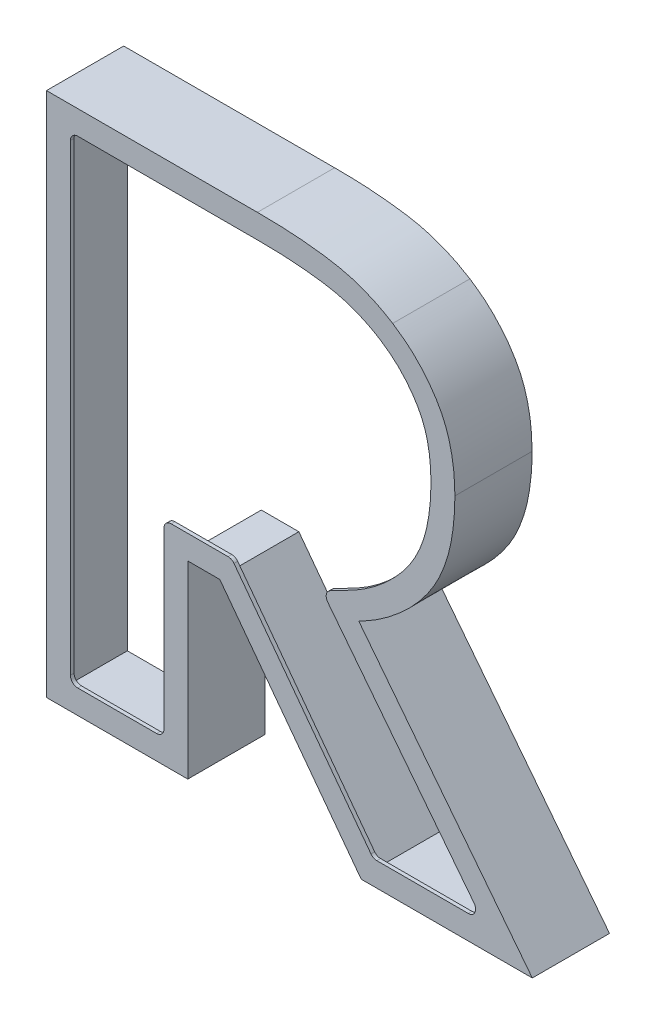
SolidWorks part; units mm, degrees
ref_plane "Front Plane" through (0, 0, 0) normal (0, 0, 1) x (1, 0, 0)
ref_plane "Top Plane" through (0, 0, 0) normal (0, 1, 0) x (1, 0, 0)
ref_plane "Right Plane" through (0, 0, 0) normal (1, 0, 0) x (0, 0, -1)
sketch "Sketch1" plane through (0, 0, 0) normal (0, 0, 1) x (1, 0, 0)
  line L65 (2984.2848, -1502.5826) -> (2926.9066, -1502.5826)
  line L66 (3059.0757, -1645.5826) -> (3011.8589, -1585.1045)
  line L67 (3012.5251, -1645.5826) -> (3059.0757, -1645.5826)
  line L68 (2974.0639, -1594.1902) -> (3012.5251, -1645.5826)
  line L69 (2965.3497, -1594.1902) -> (2974.0639, -1594.1902)
  line L70 (2965.3497, -1645.5826) -> (2965.3497, -1594.1902)
  line L71 (2926.9066, -1502.5826) -> (2926.9066, -1645.5826)
  line L72 (2926.9066, -1645.5826) -> (2965.3497, -1645.5826)
  line L73 (2984.2848, -1502.5826) -> (2926.9066, -1502.5826)
  line L74 (3059.0757, -1645.5826) -> (3011.8589, -1585.1045)
  line L75 (3012.5251, -1645.5826) -> (3059.0757, -1645.5826)
  line L76 (2974.0639, -1594.1902) -> (3012.5251, -1645.5826)
  line L77 (2965.3497, -1594.1902) -> (2974.0639, -1594.1902)
  line L78 (2965.3497, -1645.5826) -> (2965.3497, -1594.1902)
  line L79 (2926.9066, -1502.5826) -> (2926.9066, -1645.5826)
  line L80 (2926.9066, -1645.5826) -> (2965.3497, -1645.5826)
  spline S12 degree 3 poles (4010.2252, 226.3822) (3055.0458, -1622.3728) (3054.8193, -1526.8514) (3015.5085, -1507.3041) (3014.0398, -1506.6932) (3011.791, -1505.8699) (3011.0366, -1505.6141) (3009.5173, -1505.1475) (3008.752, -1504.9375) (3006.4396, -1504.3769) (3004.8773, -1504.0899) (3001.7298, -1503.6105) (3000.1482, -1503.4184) (2996.9859, -1503.0865) (2995.4028, -1502.9517) (2992.2324, -1502.7488) (2990.6451, -1502.6808) (2920.7722, -1501.0072) (2849.3372, -1549.2207) (2910.0267, 492.5285) knots -3.206592 -3.206592 -3.206592 -3.206592 0.125 0.125 0.25 0.25 0.3125 0.3125 0.375 0.375 0.5 0.5 0.625 0.625 0.75 0.75 0.875 0.875 6.24585 6.24585 6.24585 6.24585 only from (3021.0882, -1510.3488) to (2984.2848, -1502.5826)
  spline S13 degree 3 poles (5028.8784, -1369.879) (2970.5907, -1642.9502) (3041.5752, -1584.5412) (3037.6687, -1536.1925) (3037.4469, -1534.6286) (3036.9787, -1532.3038) (3036.8014, -1531.5321) (3036.3993, -1529.9963) (3036.1734, -1529.2322) (3035.7857, -1528.0937) (3035.648, -1527.7149) (3035.3574, -1526.9685) (3035.2042, -1526.6001) (3034.7222, -1525.5079) (3034.3715, -1524.7971) (3033.2459, -1522.7083) (3032.402, -1521.371) (3031.0037, -1519.4436) (3030.5147, -1518.8147) (3029.4925, -1517.583) (3028.9623, -1516.984) (3027.3291, -1515.2424) (3026.1832, -1514.1467) (2993.5272, -1487.5279) (2903.1028, -1529.3957) (4246.4092, 68.7534) knots -3.578397 -3.578397 -3.578397 -3.578397 0.125 0.125 0.25 0.25 0.3125 0.3125 0.375 0.375 0.40625 0.40625 0.4375 0.4375 0.5 0.5 0.625 0.625 0.6875 0.6875 0.75 0.75 0.875 0.875 4.072965 4.072965 4.072965 4.072965 only from (3038.0082, -1542.5336) to (3021.0882, -1510.3488)
  spline S14 degree 3 poles (4034.7201, -3301.2243) (2880.5558, -1576.6127) (2968.7745, -1609.9372) (3015.7268, -1582.9688) (3016.663, -1582.3914) (3018.488, -1581.1693) (3019.3784, -1580.5271) (3021.1207, -1579.1881) (3021.9731, -1578.492) (3023.2238, -1577.4084) (3023.6359, -1577.0404) (3024.4498, -1576.2899) (3024.8522, -1575.9067) (3026.0366, -1574.7407) (3026.7961, -1573.9403) (3028.2531, -1572.292) (3028.9507, -1571.4442) (3030.2824, -1569.7001) (3030.9178, -1568.8046) (3032.1132, -1566.9561) (3032.671, -1566.0013) (3033.6978, -1564.0237) (3034.1575, -1563.0166) (3034.9889, -1560.9765) (3035.3648, -1559.9441) (3036.0401, -1557.8555) (3036.3372, -1556.7985) (3036.8466, -1554.6582) (3037.0571, -1553.5743) (3037.3186, -1551.9316) (3037.3974, -1551.381) (3037.5426, -1550.28) (3037.6098, -1549.7291) (3037.7908, -1548.075) (3037.8815, -1546.9701) (3039.8713, -1502.1646) (2987.2068, -1454.5687) (5036.4914, -1557.0312) knots -2.944012 -2.944012 -2.944012 -2.944012 0.0625 0.0625 0.125 0.125 0.1875 0.1875 0.25 0.25 0.28125 0.28125 0.3125 0.3125 0.375 0.375 0.4375 0.4375 0.5 0.5 0.5625 0.5625 0.625 0.625 0.6875 0.6875 0.75 0.75 0.8125 0.8125 0.84375 0.84375 0.875 0.875 0.9375 0.9375 3.402691 3.402691 3.402691 3.402691 only from (3011.8589, -1585.1045) to (3038.0082, -1542.5336)
  spline S15 degree 3 poles (3021.0882, -1510.3488) (3019.7203, -1509.5327) (3018.3517, -1508.7179) (3015.5085, -1507.3041) (3014.0398, -1506.6932) (3011.791, -1505.8699) (3011.0366, -1505.6141) (3009.5173, -1505.1475) (3008.752, -1504.9375) (3006.4396, -1504.3769) (3004.8773, -1504.0899) (3001.7298, -1503.6105) (3000.1482, -1503.4184) (2996.9859, -1503.0865) (2995.4028, -1502.9517) (2992.2324, -1502.7488) (2990.6451, -1502.6808) (2987.4667, -1502.6047) (2985.8757, -1502.5936) (2984.2848, -1502.5826) knots 0 0 0 0 0.125 0.125 0.25 0.25 0.3125 0.3125 0.375 0.375 0.5 0.5 0.625 0.625 0.75 0.75 0.875 0.875 1 1 1 1
  spline S16 degree 3 poles (3038.0082, -1542.5336) (3037.9662, -1540.9417) (3037.9238, -1539.3498) (3037.6687, -1536.1925) (3037.4469, -1534.6286) (3036.9787, -1532.3038) (3036.8014, -1531.5321) (3036.3993, -1529.9963) (3036.1734, -1529.2322) (3035.7857, -1528.0937) (3035.648, -1527.7149) (3035.3574, -1526.9685) (3035.2042, -1526.6001) (3034.7222, -1525.5079) (3034.3715, -1524.7971) (3033.2459, -1522.7083) (3032.402, -1521.371) (3031.0037, -1519.4436) (3030.5147, -1518.8147) (3029.4925, -1517.583) (3028.9623, -1516.984) (3027.3291, -1515.2424) (3026.1832, -1514.1467) (3023.7263, -1512.1441) (3022.4078, -1511.2458) (3021.0882, -1510.3488) knots 0 0 0 0 0.125 0.125 0.25 0.25 0.3125 0.3125 0.375 0.375 0.40625 0.40625 0.4375 0.4375 0.5 0.5 0.625 0.625 0.6875 0.6875 0.75 0.75 0.875 0.875 1 1 1 1
  spline S17 degree 3 poles (3011.8589, -1585.1045) (3012.84, -1584.5906) (3013.8144, -1584.0672) (3015.7268, -1582.9688) (3016.663, -1582.3914) (3018.488, -1581.1693) (3019.3784, -1580.5271) (3021.1207, -1579.1881) (3021.9731, -1578.492) (3023.2238, -1577.4084) (3023.6359, -1577.0404) (3024.4498, -1576.2899) (3024.8522, -1575.9067) (3026.0366, -1574.7407) (3026.7961, -1573.9403) (3028.2531, -1572.292) (3028.9507, -1571.4442) (3030.2824, -1569.7001) (3030.9178, -1568.8046) (3032.1132, -1566.9561) (3032.671, -1566.0013) (3033.6978, -1564.0237) (3034.1575, -1563.0166) (3034.9889, -1560.9765) (3035.3648, -1559.9441) (3036.0401, -1557.8555) (3036.3372, -1556.7985) (3036.8466, -1554.6582) (3037.0571, -1553.5743) (3037.3186, -1551.9316) (3037.3974, -1551.381) (3037.5426, -1550.28) (3037.6098, -1549.7291) (3037.7908, -1548.075) (3037.8815, -1546.9701) (3037.9799, -1544.7543) (3037.994, -1543.644) (3038.0082, -1542.5336) knots 0 0 0 0 0.0625 0.0625 0.125 0.125 0.1875 0.1875 0.25 0.25 0.28125 0.28125 0.3125 0.3125 0.375 0.375 0.4375 0.4375 0.5 0.5 0.5625 0.5625 0.625 0.625 0.6875 0.6875 0.75 0.75 0.8125 0.8125 0.84375 0.84375 0.875 0.875 0.9375 0.9375 1 1 1 1
  dimension "D1" = 1.5
extrude "Boss-Extrude1" add sketch "Sketch1" along normal blind 1 and the other way blind 20
sketch3d "3DSketch1"
  line L0 (2933.4066, -1639.0826, -20) -> (2933.4066, -1509.0826, -20)
  line L1 (2933.4066, -1509.0826, -20) -> (2984.2623, -1509.0826, -20)
  line L2 (3001.9399, -1582.9622, -20) -> (3045.7546, -1639.0826, -20)
  line L3 (3045.7546, -1639.0826, -20) -> (3015.7793, -1639.0826, -20)
  line L4 (3015.7793, -1639.0826, -20) -> (2977.3181, -1587.6902, -20)
  line L5 (2977.3181, -1587.6902, -20) -> (2958.8497, -1587.6902, -20)
  line L6 (2958.8497, -1587.6902, -20) -> (2958.8497, -1639.0826, -20)
  line L7 (2958.8497, -1639.0826, -20) -> (2933.4066, -1639.0826, -20)
  line L8 (2933.4066, -1639.0826, -20) -> (2933.4066, -1509.0826, -20)
  line L9 (2933.4066, -1509.0826, -20) -> (2984.2623, -1509.0826, -20)
  line L10 (3001.9399, -1582.9622, -20) -> (3045.7546, -1639.0826, -20)
  line L11 (3045.7546, -1639.0826, -20) -> (3015.7793, -1639.0826, -20)
  line L12 (3015.7793, -1639.0826, -20) -> (2977.3181, -1587.6902, -20)
  line L13 (2977.3181, -1587.6902, -20) -> (2958.8497, -1587.6902, -20)
  line L14 (2958.8497, -1587.6902, -20) -> (2958.8497, -1639.0826, -20)
  line L15 (2958.8497, -1639.0826, -20) -> (2933.4066, -1639.0826, -20)
  spline S0 degree 5 poles (2819.8288, -522.7172, -20) (2853.7575, -1119.7339, -20) (2887.1266, -1415.5067, -20) (2920.1329, -1511.4077, -20) (2953.5716, -1508.7635, -20) (2987.0156, -1509.1056, -20) (2987.6268, -1509.1137, -20) (2989.1582, -1509.1414, -20) (2990.6891, -1509.1929, -20) (2991.6088, -1509.2327, -20) (2993.4255, -1509.3293, -20) (2995.2401, -1509.4623, -20) (2996.1358, -1509.5371, -20) (2997.8557, -1509.6988, -20) (2999.5718, -1509.8956, -20) (3000.394, -1509.9986, -20) (3001.9348, -1510.209, -20) (3003.4713, -1510.4535, -20) (3004.1871, -1510.5784, -20) (3005.5524, -1510.8448, -20) (3006.9041, -1511.1753, -20) (3007.5462, -1511.3478, -20) (3008.7841, -1511.7105, -20) (3010.0046, -1512.1276, -20) (3010.5917, -1512.3421, -20) (3011.7964, -1512.8097, -20) (3012.9815, -1513.3255, -20) (3013.5869, -1513.6058, -20) (3014.5791, -1514.0963, -20) (3015.5475, -1514.632, -20) (3015.9294, -1514.8501, -20) (3033.1615, -1524.9039, -20) (3048.1266, -1538.4031, -20) (3117.2106, -1468.8543, -20) (3297.3605, -1230.51, -20) (3645.201, -737.313, -20) knots -4.715851 -4.715851 -4.715851 -4.715851 -4.715851 -4.715851 0.044396 0.044396 0.044396 0.133005 0.133005 0.133005 0.266452 0.266452 0.266452 0.396744 0.396744 0.396744 0.516875 0.516875 0.516875 0.62218 0.62218 0.62218 0.718504 0.718504 0.718504 0.809085 0.809085 0.809085 0.905745 0.905745 0.905745 0.96949 0.96949 0.96949 3.796826 3.796826 3.796826 3.796826 3.796826 3.796826 only from (2984.2623, -1509.0826, -20) to (3017.593, -1515.8324, -20)
  spline S1 degree 5 poles (3480.3723, -629.3626, -20) (3167.4678, -1144.7276, -20) (3020.7923, -1405.2812, -20) (2984.344, -1496.8596, -20) (3002.4839, -1505.4164, -20) (3018.8499, -1516.6924, -20) (3019.1458, -1516.8992, -20) (3019.8785, -1517.4231, -20) (3020.5924, -1517.9735, -20) (3021.0125, -1518.3132, -20) (3021.8853, -1519.0559, -20) (3022.7145, -1519.8467, -20) (3023.1418, -1520.2765, -20) (3024.0421, -1521.2263, -20) (3024.8992, -1522.2153, -20) (3025.3455, -1522.7578, -20) (3026.2492, -1523.9202, -20) (3027.0797, -1525.1369, -20) (3027.4924, -1525.7876, -20) (3028.2695, -1527.115, -20) (3028.9466, -1528.4976, -20) (3029.2572, -1529.2003, -20) (3029.789, -1530.5535, -20) (3030.2052, -1531.9453, -20) (3030.3797, -1532.6089, -20) (3030.6763, -1533.8777, -20) (3030.9206, -1535.1564, -20) (3031.0233, -1535.7637, -20) (3031.1924, -1536.9264, -20) (3031.3057, -1538.096, -20) (3031.3489, -1538.6538, -20) (3031.407, -1539.5937, -20) (3031.4462, -1540.5342, -20) (3031.4597, -1540.916, -20) (3032.1523, -1563.1752, -20) (3029.8681, -1585.5386, -20) (3127.0415, -1604.037, -20) (3425.927, -1615.4717, -20) (4028.7841, -1616.268, -20) knots -3.059006 -3.059006 -3.059006 -3.059006 -3.059006 -3.059006 0.025326 0.025326 0.025326 0.08238 0.08238 0.08238 0.167715 0.167715 0.167715 0.263441 0.263441 0.263441 0.374387 0.374387 0.374387 0.496016 0.496016 0.496016 0.617184 0.617184 0.617184 0.725488 0.725488 0.725488 0.822804 0.822804 0.822804 0.911198 0.911198 0.911198 0.971595 0.971595 0.971595 4.43181 4.43181 4.43181 4.43181 4.43181 4.43181 only from (3017.593, -1515.8324, -20) to (3031.5071, -1542.5778, -20)
  spline S2 degree 5 poles (4023.0375, -1412.7278, -20) (3422.9811, -1447.5677, -20) (3125.6698, -1475.8448, -20) (3029.2531, -1499.7946, -20) (3031.876, -1522.0128, -20) (3031.4813, -1544.296, -20) (3031.4718, -1544.6979, -20) (3031.4389, -1545.7022, -20) (3031.3745, -1546.7051, -20) (3031.326, -1547.3062, -20) (3031.2139, -1548.4867, -20) (3031.0747, -1549.6641, -20) (3030.999, -1550.2418, -20) (3030.8057, -1551.572, -20) (3030.5651, -1552.8949, -20) (3030.4117, -1553.6411, -20) (3030.0308, -1555.2814, -20) (3029.5482, -1556.8969, -20) (3029.2538, -1557.7725, -20) (3028.5399, -1559.6771, -20) (3027.6834, -1561.5228, -20) (3027.173, -1562.5093, -20) (3026.0602, -1564.4432, -20) (3024.772, -1566.2641, -20) (3024.0859, -1567.1519, -20) (3022.7129, -1568.7966, -20) (3021.2405, -1570.3493, -20) (3020.5183, -1571.0683, -20) (3019.1247, -1572.381, -20) (3017.6682, -1573.623, -20) (3016.9732, -1574.1878, -20) (3015.6472, -1575.2129, -20) (3014.2747, -1576.1753, -20) (3013.6256, -1576.6093, -20) (3012.5274, -1577.3081, -20) (3011.4033, -1577.9637, -20) (3010.9499, -1578.2199, -20) (3010.2572, -1578.6007, -20) (3009.5591, -1578.9709, -20) (3009.3205, -1579.0964, -20) (2830.519, -1672.7499, -20) (2651.7174, -1766.4033, -20) (2473.1546, -1859.9318, -20) (2294.5912, -1953.4604, -20) (2116.1321, -2046.9452, -20.0006) knots -2.02361 -2.02361 -2.02361 -2.02361 -2.02361 -2.02361 0.017053 0.017053 0.017053 0.054543 0.054543 0.054543 0.110764 0.110764 0.110764 0.165093 0.165093 0.165093 0.236106 0.236106 0.236106 0.322069 0.322069 0.322069 0.425384 0.425384 0.425384 0.529778 0.529778 0.529778 0.624717 0.624717 0.624717 0.708181 0.708181 0.708181 0.780957 0.780957 0.780957 0.829506 0.829506 0.829506 0.854647 0.854647 0.854647 19.65415 19.65415 19.65415 19.65415 19.65415 19.65415 only from (3031.5071, -1542.5778, -20) to (3001.9399, -1582.9622, -20)
  spline S3 degree 5 poles (2984.2623, -1509.0826, -20) (2984.5685, -1509.0847, -20) (2984.8747, -1509.0868, -20) (2985.1809, -1509.089, -20) (2986.0983, -1509.0962, -20) (2987.0156, -1509.1056, -20) (2987.6268, -1509.1137, -20) (2989.1582, -1509.1414, -20) (2990.6891, -1509.1929, -20) (2991.6088, -1509.2327, -20) (2993.4255, -1509.3293, -20) (2995.2401, -1509.4623, -20) (2996.1358, -1509.5371, -20) (2997.8557, -1509.6988, -20) (2999.5718, -1509.8956, -20) (3000.394, -1509.9986, -20) (3001.9348, -1510.209, -20) (3003.4713, -1510.4535, -20) (3004.1871, -1510.5784, -20) (3005.5524, -1510.8448, -20) (3006.9041, -1511.1753, -20) (3007.5462, -1511.3478, -20) (3008.7841, -1511.7105, -20) (3010.0046, -1512.1276, -20) (3010.5917, -1512.3421, -20) (3011.7964, -1512.8097, -20) (3012.9815, -1513.3255, -20) (3013.5869, -1513.6058, -20) (3014.5791, -1514.0963, -20) (3015.5475, -1514.632, -20) (3015.9294, -1514.8501, -20) (3016.4912, -1515.1779, -20) (3017.0506, -1515.5093, -20) (3017.2315, -1515.6169, -20) (3017.4123, -1515.7246, -20) (3017.593, -1515.8324, -20) knots 0 0 0 0 0 0 0.044396 0.044396 0.044396 0.133005 0.133005 0.133005 0.266452 0.266452 0.266452 0.396744 0.396744 0.396744 0.516875 0.516875 0.516875 0.62218 0.62218 0.62218 0.718504 0.718504 0.718504 0.809085 0.809085 0.809085 0.905745 0.905745 0.905745 0.96949 0.96949 0.96949 1 1 1 1 1 1
  spline S4 degree 5 poles (3017.593, -1515.8324, -20) (3017.7255, -1515.9225, -20) (3017.8579, -1516.0126, -20) (3017.9903, -1516.1028, -20) (3018.4207, -1516.3967, -20) (3018.8499, -1516.6924, -20) (3019.1458, -1516.8992, -20) (3019.8785, -1517.4231, -20) (3020.5924, -1517.9735, -20) (3021.0125, -1518.3132, -20) (3021.8853, -1519.0559, -20) (3022.7145, -1519.8467, -20) (3023.1418, -1520.2765, -20) (3024.0421, -1521.2263, -20) (3024.8992, -1522.2153, -20) (3025.3455, -1522.7578, -20) (3026.2492, -1523.9202, -20) (3027.0797, -1525.1369, -20) (3027.4924, -1525.7876, -20) (3028.2695, -1527.115, -20) (3028.9466, -1528.4976, -20) (3029.2572, -1529.2003, -20) (3029.789, -1530.5535, -20) (3030.2052, -1531.9453, -20) (3030.3797, -1532.6089, -20) (3030.6763, -1533.8777, -20) (3030.9206, -1535.1564, -20) (3031.0233, -1535.7637, -20) (3031.1924, -1536.9264, -20) (3031.3057, -1538.096, -20) (3031.3489, -1538.6538, -20) (3031.407, -1539.5937, -20) (3031.4462, -1540.5342, -20) (3031.4597, -1540.916, -20) (3031.4771, -1541.4775, -20) (3031.4927, -1542.039, -20) (3031.4976, -1542.2186, -20) (3031.5023, -1542.3982, -20) (3031.5071, -1542.5778, -20) knots 0 0 0 0 0 0 0.025326 0.025326 0.025326 0.08238 0.08238 0.08238 0.167715 0.167715 0.167715 0.263441 0.263441 0.263441 0.374387 0.374387 0.374387 0.496016 0.496016 0.496016 0.617184 0.617184 0.617184 0.725488 0.725488 0.725488 0.822804 0.822804 0.822804 0.911198 0.911198 0.911198 0.971595 0.971595 0.971595 1 1 1 1 1 1
  spline S5 degree 5 poles (3031.5071, -1542.5778, -20) (3031.5047, -1542.7607, -20) (3031.5024, -1542.9435, -20) (3031.4999, -1543.1264, -20) (3031.4916, -1543.7111, -20) (3031.4813, -1544.296, -20) (3031.4718, -1544.6979, -20) (3031.4389, -1545.7022, -20) (3031.3745, -1546.7051, -20) (3031.326, -1547.3062, -20) (3031.2139, -1548.4867, -20) (3031.0747, -1549.6641, -20) (3030.999, -1550.2418, -20) (3030.8057, -1551.572, -20) (3030.5651, -1552.8949, -20) (3030.4117, -1553.6411, -20) (3030.0308, -1555.2814, -20) (3029.5482, -1556.8969, -20) (3029.2538, -1557.7725, -20) (3028.5399, -1559.6771, -20) (3027.6834, -1561.5228, -20) (3027.173, -1562.5093, -20) (3026.0602, -1564.4432, -20) (3024.772, -1566.2641, -20) (3024.0859, -1567.1519, -20) (3022.7129, -1568.7966, -20) (3021.2405, -1570.3493, -20) (3020.5183, -1571.0683, -20) (3019.1247, -1572.381, -20) (3017.6682, -1573.623, -20) (3016.9732, -1574.1878, -20) (3015.6472, -1575.2129, -20) (3014.2747, -1576.1753, -20) (3013.6256, -1576.6093, -20) (3012.5274, -1577.3081, -20) (3011.4033, -1577.9637, -20) (3010.9499, -1578.2199, -20) (3010.2572, -1578.6007, -20) (3009.5591, -1578.9709, -20) (3009.3205, -1579.0964, -20) (3007.7011, -1579.9446, -20) (3006.0817, -1580.7928, -20) (3004.7011, -1581.5159, -20) (3003.3205, -1582.2391, -20) (3001.9399, -1582.9622, -20) knots 0 0 0 0 0 0 0.017053 0.017053 0.017053 0.054543 0.054543 0.054543 0.110764 0.110764 0.110764 0.165093 0.165093 0.165093 0.236106 0.236106 0.236106 0.322069 0.322069 0.322069 0.425384 0.425384 0.425384 0.529778 0.529778 0.529778 0.624717 0.624717 0.624717 0.708181 0.708181 0.708181 0.780957 0.780957 0.780957 0.829506 0.829506 0.829506 0.854647 0.854647 0.854647 1 1 1 1 1 1
  dimension "D1" = 6.5
extrude "Cut-Extrude1" cut sketch "3DSketch1" along direction (0, 0, 1) on the side against the normal through all
sketch3d "3DSketch2"
  line L0 (2927.9066, -1644.5826, -20) -> (2927.9066, -1503.5826, -20)
  line L1 (2927.9066, -1503.5826, -20) -> (2984.2813, -1503.5826, -20)
  line L2 (3010.3329, -1584.7749, -20) -> (3057.0263, -1644.5826, -20)
  line L3 (3057.0263, -1644.5826, -20) -> (3013.0258, -1644.5826, -20)
  line L4 (3013.0258, -1644.5826, -20) -> (2974.5645, -1593.1902, -20)
  line L5 (2974.5645, -1593.1902, -20) -> (2964.3497, -1593.1902, -20)
  line L6 (2964.3497, -1593.1902, -20) -> (2964.3497, -1644.5826, -20)
  line L7 (2964.3497, -1644.5826, -20) -> (2927.9066, -1644.5826, -20)
  line L8 (2927.9066, -1644.5826, -20) -> (2927.9066, -1503.5826, -20)
  line L9 (2927.9066, -1503.5826, -20) -> (2984.2813, -1503.5826, -20)
  line L10 (3010.3329, -1584.7749, -20) -> (3057.0263, -1644.5826, -20)
  line L11 (3057.0263, -1644.5826, -20) -> (3013.0258, -1644.5826, -20)
  line L12 (3013.0258, -1644.5826, -20) -> (2974.5645, -1593.1902, -20)
  line L13 (2974.5645, -1593.1902, -20) -> (2964.3497, -1593.1902, -20)
  line L14 (2964.3497, -1593.1902, -20) -> (2964.3497, -1644.5826, -20)
  line L15 (2964.3497, -1644.5826, -20) -> (2927.9066, -1644.5826, -20)
  spline S0 degree 5 poles (2821.2053, -516.98, -20) (2854.4791, -1114.2714, -20) (2887.5083, -1410.1132, -20) (2920.3528, -1505.9713, -20) (2953.7384, -1503.2589, -20) (2987.1267, -1503.6065, -20) (2987.7587, -1503.6151, -20) (2989.347, -1503.6443, -20) (2990.9347, -1503.6981, -20) (2991.8903, -1503.7396, -20) (2993.7895, -1503.8409, -20) (2995.6864, -1503.9803, -20) (2996.6286, -1504.0591, -20) (2998.451, -1504.2306, -20) (3000.2695, -1504.4392, -20) (3001.1476, -1504.5494, -20) (3002.8178, -1504.7784, -20) (3004.4829, -1505.0462, -20) (3005.2718, -1505.1854, -20) (3006.796, -1505.4853, -20) (3008.3052, -1505.8555, -20) (3009.0323, -1506.0511, -20) (3010.4494, -1506.4667, -20) (3011.8467, -1506.944, -20) (3012.5265, -1507.1923, -20) (3013.9017, -1507.7265, -20) (3015.2544, -1508.316, -20) (3015.9364, -1508.6317, -20) (3017.0528, -1509.1825, -20) (3018.1435, -1509.7823, -20) (3018.5727, -1510.0261, -20) (3035.7468, -1519.9985, -20) (3050.4921, -1533.7771, -20) (3118.2282, -1463.5909, -20) (3294.9883, -1222.5404, -20) (3636.435, -723.3837, -20) knots -4.315245 -4.315245 -4.315245 -4.315245 -4.315245 -4.315245 0.04207 0.04207 0.04207 0.126145 0.126145 0.126145 0.253365 0.253365 0.253365 0.379111 0.379111 0.379111 0.496825 0.496825 0.496825 0.603333 0.603333 0.603333 0.703418 0.703418 0.703418 0.799647 0.799647 0.799647 0.899545 0.899545 0.899545 0.965179 0.965179 0.965179 3.540111 3.540111 3.540111 3.540111 3.540111 3.540111 only from (2984.2813, -1503.5826, -20) to (3020.5505, -1511.1924, -20)
  spline S1 degree 5 poles (3488.6979, -627.5467, -20) (3173.0172, -1142.2354, -20) (3024.9554, -1402.1034, -20) (2988.0007, -1493.0484, -20) (3006.0312, -1501.1426, -20) (3022.0845, -1512.2429, -20) (3022.4204, -1512.4789, -20) (3023.2577, -1513.0808, -20) (3024.0732, -1513.7129, -20) (3024.5552, -1514.1046, -20) (3025.5739, -1514.9736, -20) (3026.5437, -1515.8965, -20) (3027.0506, -1516.405, -20) (3028.1162, -1517.5265, -20) (3029.129, -1518.696, -20) (3029.655, -1519.3366, -20) (3030.7303, -1520.723, -20) (3031.7177, -1522.1743, -20) (3032.2125, -1522.9577, -20) (3033.145, -1524.5571, -20) (3033.9579, -1526.2222, -20) (3034.3315, -1527.0692, -20) (3034.9716, -1528.6965, -20) (3035.4772, -1530.369, -20) (3035.6892, -1531.1645, -20) (3036.0443, -1532.6646, -20) (3036.3345, -1534.1775, -20) (3036.4543, -1534.8848, -20) (3036.6474, -1536.2105, -20) (3036.7788, -1537.5438, -20) (3036.8283, -1538.1645, -20) (3036.8947, -1539.2018, -20) (3036.939, -1540.2398, -20) (3036.9541, -1540.656, -20) (3037.6613, -1563.0359, -20) (3035.2587, -1585.5067, -20) (3132.2633, -1604.6593, -20) (3430.9882, -1617.924, -20) (4033.808, -1622.3275, -20) knots -2.5462 -2.5462 -2.5462 -2.5462 -2.5462 -2.5462 0.02798 0.02798 0.02798 0.083286 0.083286 0.083286 0.16691 0.16691 0.16691 0.263593 0.263593 0.263593 0.375162 0.375162 0.375162 0.499816 0.499816 0.499816 0.624269 0.624269 0.624269 0.735047 0.735047 0.735047 0.831661 0.831661 0.831661 0.915522 0.915522 0.915522 0.971644 0.971644 0.971644 3.932644 3.932644 3.932644 3.932644 3.932644 3.932644 only from (3020.5505, -1511.1924, -20) to (3037.008, -1542.5404, -20)
  spline S2 degree 5 poles (4029.9089, -1423.741, -20) (3428.5649, -1452.7723, -20) (3130.8532, -1477.9958, -20) (3034.5299, -1500.688, -20) (3037.3881, -1522.5708, -20) (3036.9781, -1544.4946, -20) (3036.9673, -1544.9318, -20) (3036.9302, -1546.0245, -20) (3036.8597, -1547.1157, -20) (3036.8068, -1547.7699, -20) (3036.6834, -1549.0725, -20) (3036.5296, -1550.3717, -20) (3036.4447, -1551.0181, -20) (3036.2258, -1552.5176, -20) (3035.9527, -1554.0088, -20) (3035.7777, -1554.8546, -20) (3035.3374, -1556.7424, -20) (3034.7808, -1558.6015, -20) (3034.437, -1559.6216, -20) (3033.6048, -1561.8371, -20) (3032.6067, -1563.984, -20) (3032.0133, -1565.1302, -20) (3030.7252, -1567.3699, -20) (3029.2379, -1569.4815, -20) (3028.449, -1570.5076, -20) (3026.8845, -1572.3902, -20) (3025.2041, -1574.1665, -20) (3024.3883, -1574.98, -20) (3022.8176, -1576.4614, -20) (3021.1753, -1577.862, -20) (3020.3938, -1578.4968, -20) (3018.9123, -1579.6416, -20) (3017.3791, -1580.7165, -20) (3016.6595, -1581.1979, -20) (3015.4433, -1581.9729, -20) (3014.1989, -1582.7014, -20) (3013.6975, -1582.9857, -20) (3012.9371, -1583.405, -20) (3012.1703, -1583.8119, -20) (3011.912, -1583.9478, -20) (2875.5448, -1655.3748, -20) (2739.1777, -1726.8018, -20) (2603.0691, -1798.0933, -20) (2467.0519, -1869.483, -20.0007) (2099.994, -1811.1045, -19.418) knots -2.005281 -2.005281 -2.005281 -2.005281 -2.005281 -2.005281 0.020358 0.020358 0.020358 0.061581 0.061581 0.061581 0.123429 0.123429 0.123429 0.184886 0.184886 0.184886 0.266273 0.266273 0.266273 0.367536 0.367536 0.367536 0.488897 0.488897 0.488897 0.610646 0.610646 0.610646 0.71914 0.71914 0.71914 0.813999 0.813999 0.813999 0.895562 0.895562 0.895562 0.949879 0.949879 0.949879 0.977396 0.977396 0.977396 15.462532 15.462532 15.462532 15.462532 15.462532 15.462532 only from (3037.008, -1542.5404, -20) to (3010.3329, -1584.7749, -20)
  spline S3 degree 5 poles (2984.2813, -1503.5826, -20) (2984.5976, -1503.5848, -20) (2984.9139, -1503.587, -20) (2985.2301, -1503.5893, -20) (2986.1784, -1503.5967, -20) (2987.1267, -1503.6065, -20) (2987.7587, -1503.6151, -20) (2989.347, -1503.6443, -20) (2990.9347, -1503.6981, -20) (2991.8903, -1503.7396, -20) (2993.7895, -1503.8409, -20) (2995.6864, -1503.9803, -20) (2996.6286, -1504.0591, -20) (2998.451, -1504.2306, -20) (3000.2695, -1504.4392, -20) (3001.1476, -1504.5494, -20) (3002.8178, -1504.7784, -20) (3004.4829, -1505.0462, -20) (3005.2718, -1505.1854, -20) (3006.796, -1505.4853, -20) (3008.3052, -1505.8555, -20) (3009.0323, -1506.0511, -20) (3010.4494, -1506.4667, -20) (3011.8467, -1506.944, -20) (3012.5265, -1507.1923, -20) (3013.9017, -1507.7265, -20) (3015.2544, -1508.316, -20) (3015.9364, -1508.6317, -20) (3017.0528, -1509.1825, -20) (3018.1435, -1509.7823, -20) (3018.5727, -1510.0261, -20) (3019.2261, -1510.4055, -20) (3019.8759, -1510.7903, -20) (3020.1009, -1510.9242, -20) (3020.3257, -1511.0583, -20) (3020.5505, -1511.1924, -20) knots 0 0 0 0 0 0 0.04207 0.04207 0.04207 0.126145 0.126145 0.126145 0.253365 0.253365 0.253365 0.379111 0.379111 0.379111 0.496825 0.496825 0.496825 0.603333 0.603333 0.603333 0.703418 0.703418 0.703418 0.799647 0.799647 0.799647 0.899545 0.899545 0.899545 0.965179 0.965179 0.965179 1 1 1 1 1 1
  spline S4 degree 5 poles (3020.5505, -1511.1924, -20) (3020.7222, -1511.3091, -20) (3020.8939, -1511.4259, -20) (3021.0656, -1511.5428, -20) (3021.576, -1511.8914, -20) (3022.0845, -1512.2429, -20) (3022.4204, -1512.4789, -20) (3023.2577, -1513.0808, -20) (3024.0732, -1513.7129, -20) (3024.5552, -1514.1046, -20) (3025.5739, -1514.9736, -20) (3026.5437, -1515.8965, -20) (3027.0506, -1516.405, -20) (3028.1162, -1517.5265, -20) (3029.129, -1518.696, -20) (3029.655, -1519.3366, -20) (3030.7303, -1520.723, -20) (3031.7177, -1522.1743, -20) (3032.2125, -1522.9577, -20) (3033.145, -1524.5571, -20) (3033.9579, -1526.2222, -20) (3034.3315, -1527.0692, -20) (3034.9716, -1528.6965, -20) (3035.4772, -1530.369, -20) (3035.6892, -1531.1645, -20) (3036.0443, -1532.6646, -20) (3036.3345, -1534.1775, -20) (3036.4543, -1534.8848, -20) (3036.6474, -1536.2105, -20) (3036.7788, -1537.5438, -20) (3036.8283, -1538.1645, -20) (3036.8947, -1539.2018, -20) (3036.939, -1540.2398, -20) (3036.9541, -1540.656, -20) (3036.9739, -1541.2826, -20) (3036.9913, -1541.9093, -20) (3036.9969, -1542.1197, -20) (3037.0024, -1542.33, -20) (3037.008, -1542.5404, -20) knots 0 0 0 0 0 0 0.02798 0.02798 0.02798 0.083286 0.083286 0.083286 0.16691 0.16691 0.16691 0.263593 0.263593 0.263593 0.375162 0.375162 0.375162 0.499816 0.499816 0.499816 0.624269 0.624269 0.624269 0.735047 0.735047 0.735047 0.831661 0.831661 0.831661 0.915522 0.915522 0.915522 0.971644 0.971644 0.971644 1 1 1 1 1 1
  spline S5 degree 5 poles (3037.008, -1542.5404, -20) (3037.0052, -1542.7563, -20) (3037.0025, -1542.9723, -20) (3036.9996, -1543.1882, -20) (3036.9903, -1543.8414, -20) (3036.9781, -1544.4946, -20) (3036.9673, -1544.9318, -20) (3036.9302, -1546.0245, -20) (3036.8597, -1547.1157, -20) (3036.8068, -1547.7699, -20) (3036.6834, -1549.0725, -20) (3036.5296, -1550.3717, -20) (3036.4447, -1551.0181, -20) (3036.2258, -1552.5176, -20) (3035.9527, -1554.0088, -20) (3035.7777, -1554.8546, -20) (3035.3374, -1556.7424, -20) (3034.7808, -1558.6015, -20) (3034.437, -1559.6216, -20) (3033.6048, -1561.8371, -20) (3032.6067, -1563.984, -20) (3032.0133, -1565.1302, -20) (3030.7252, -1567.3699, -20) (3029.2379, -1569.4815, -20) (3028.449, -1570.5076, -20) (3026.8845, -1572.3902, -20) (3025.2041, -1574.1665, -20) (3024.3883, -1574.98, -20) (3022.8176, -1576.4614, -20) (3021.1753, -1577.862, -20) (3020.3938, -1578.4968, -20) (3018.9123, -1579.6416, -20) (3017.3791, -1580.7165, -20) (3016.6595, -1581.1979, -20) (3015.4433, -1581.9729, -20) (3014.1989, -1582.7014, -20) (3013.6975, -1582.9857, -20) (3012.9371, -1583.405, -20) (3012.1703, -1583.8119, -20) (3011.912, -1583.9478, -20) (3011.441, -1584.1945, -20) (3010.9701, -1584.4412, -20) (3010.7577, -1584.5524, -20) (3010.5453, -1584.6637, -20) (3010.3329, -1584.7749, -20) knots 0 0 0 0 0 0 0.020358 0.020358 0.020358 0.061581 0.061581 0.061581 0.123429 0.123429 0.123429 0.184886 0.184886 0.184886 0.266273 0.266273 0.266273 0.367536 0.367536 0.367536 0.488897 0.488897 0.488897 0.610646 0.610646 0.610646 0.71914 0.71914 0.71914 0.813999 0.813999 0.813999 0.895562 0.895562 0.895562 0.949879 0.949879 0.949879 0.977396 0.977396 0.977396 1 1 1 1 1 1
  dimension "D1" = 1
extrude "Cut-Extrude2" cut sketch "3DSketch2" along direction (0, 0, 1) on the side against the normal blind 20
fillet "Fillet1" radius 2 8 edges
